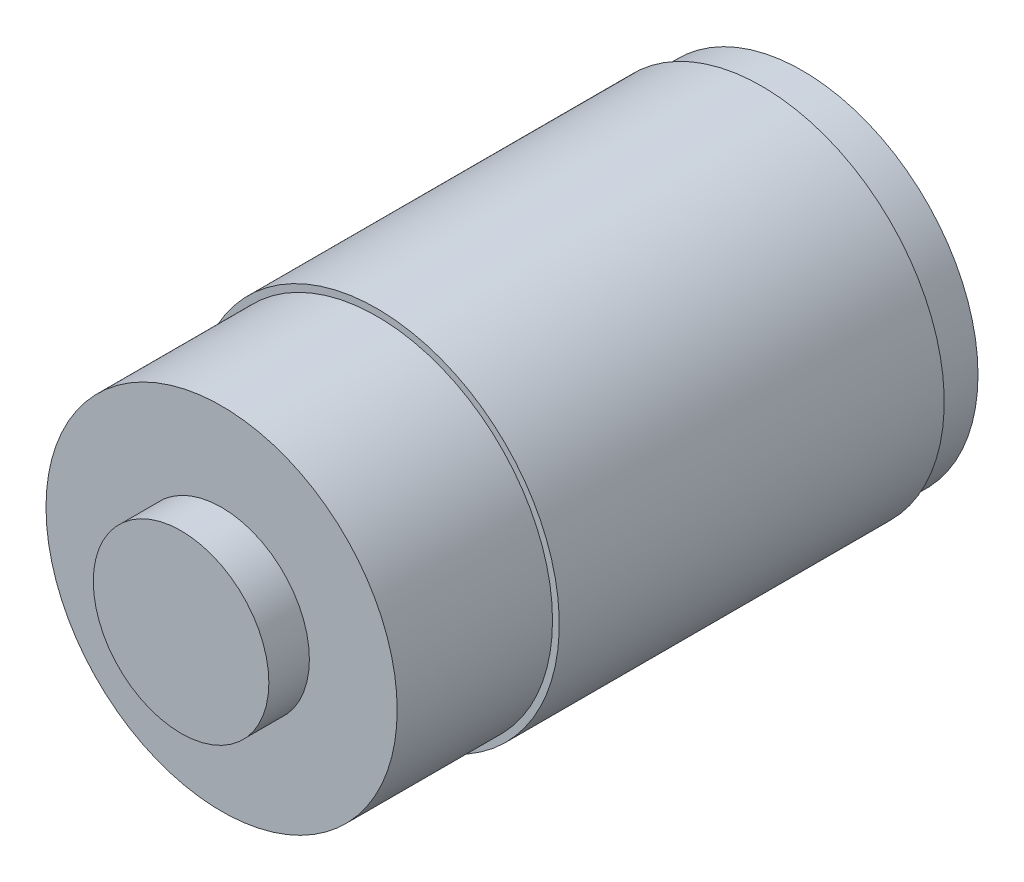
SolidWorks part; units mm, degrees
ref_plane "Front Plane" through (0, 0, 0) normal (0, 0, 1) x (1, 0, 0)
ref_plane "Top Plane" through (0, 0, 0) normal (0, 1, 0) x (1, 0, 0)
ref_plane "Right Plane" through (0, 0, 0) normal (1, 0, 0) x (0, 0, -1)
sketch "Sketch1" plane through (0, 0, 0) normal (0, 0, 1) x (1, 0, 0)
  circle A0 centre (0, 0) radius 27
  dimension "D1" = 54
extrude "Boss-Extrude1" add sketch "Sketch1" along normal blind 57
sketch "Sketch2" plane through (0, 0, 57) normal (0, 0, 1) x (1, 0, 0)
  circle A0 centre (0, 0) radius 26
  dimension "D1" = 52
extrude "Boss-Extrude2" add sketch "Sketch2" along normal blind 23
sketch "Sketch3" plane through (0, 0, 80) normal (0, 0, 1) x (1, 0, 0)
  circle A0 centre (0, 0) radius 13
  dimension "D1" = 26
extrude "Boss-Extrude3" add sketch "Sketch3" along normal blind 6
sketch "Sketch4" plane through (0, 0, 0) normal (0, 0, -1) x (-1, 0, 0)
  circle A0 centre (0, 0) radius 26
  dimension "D1" = 52
extrude "Boss-Extrude4" add sketch "Sketch4" along normal blind 6
